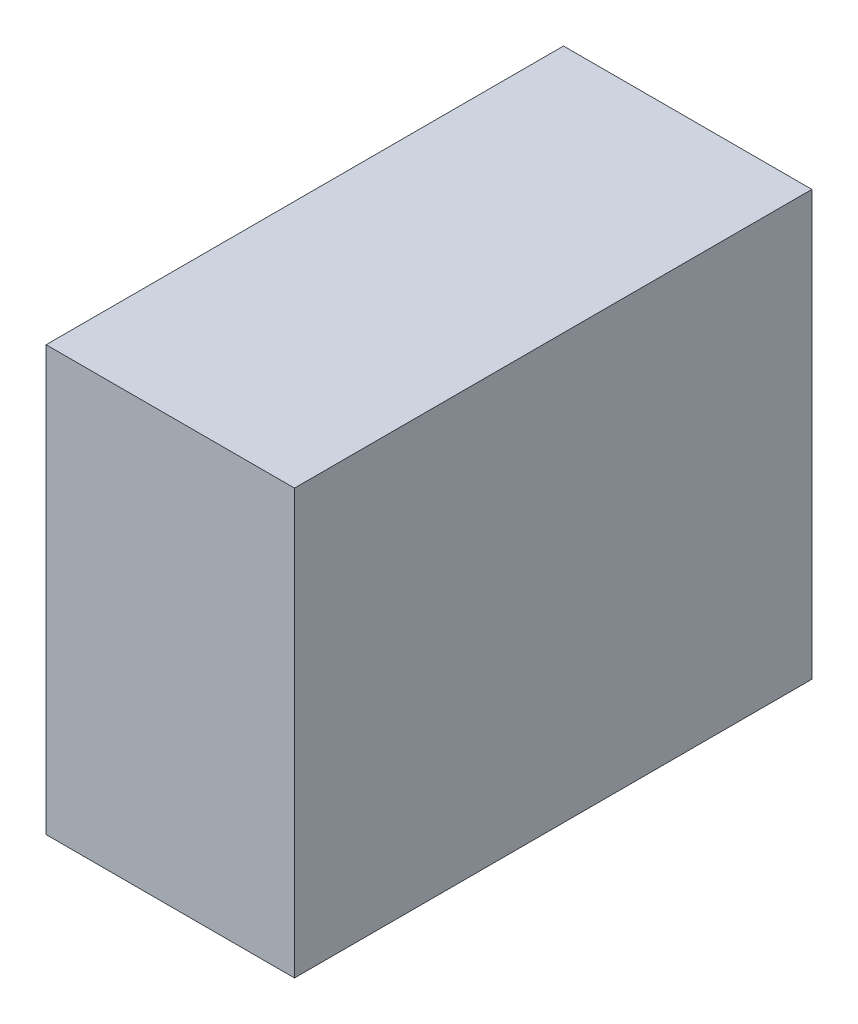
SolidWorks part; units mm, degrees
ref_plane "Front Plane" through (0, 0, 0) normal (0, 0, 1) x (1, 0, 0)
ref_plane "Top Plane" through (0, 0, 0) normal (0, 1, 0) x (1, 0, 0)
ref_plane "Right Plane" through (0, 0, 0) normal (1, 0, 0) x (0, 0, -1)
sketch "Sketch1" plane through (0, 0, 0) normal (0, 1, 0) x (1, 0, 0)
  line L1 (0, 0) -> (304.8, 0)
  line L2 (0, 0) -> (0, 635)
  line L3 (0, 635) -> (304.8, 635)
  line L4 (304.8, 0) -> (304.8, 635)
  dimension "D1" = 304.8
  dimension "D2" = 635
extrude "Boss-Extrude1" add sketch "Sketch1" along normal blind 520.7
